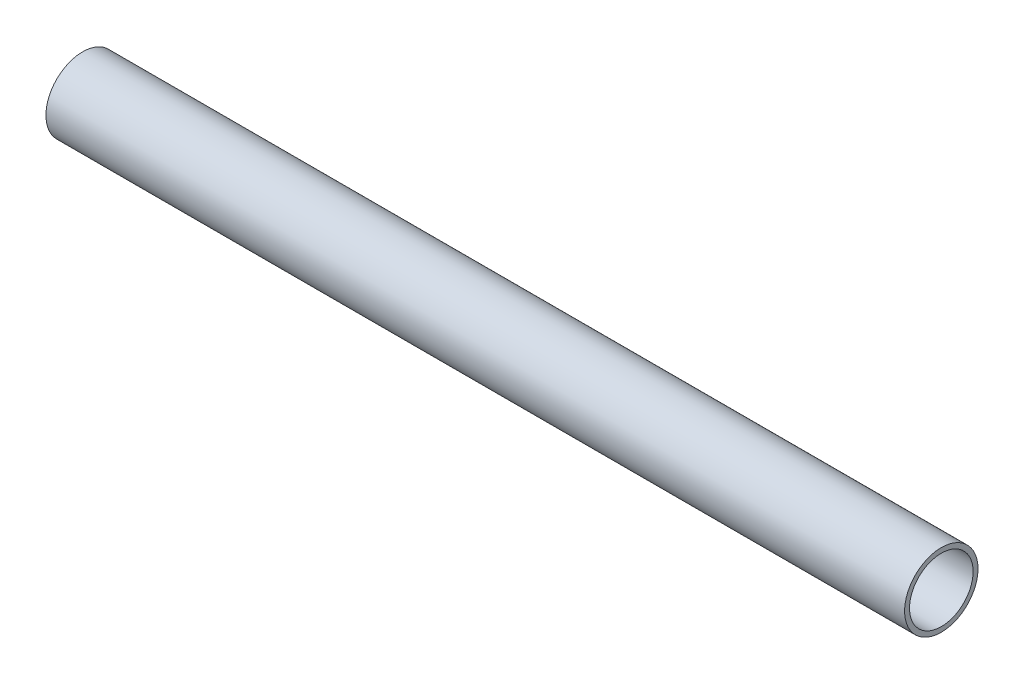
SolidWorks part; units mm, degrees
ref_plane "前视基准面" through (0, 0, 0) normal (0, 0, 1) x (1, 0, 0)
ref_plane "上视基准面" through (0, 0, 0) normal (0, 1, 0) x (1, 0, 0)
ref_plane "右视基准面" through (0, 0, 0) normal (1, 0, 0) x (0, 0, -1)
sketch "草图1" plane through (0, 0, 0) normal (1, 0, 0) x (0, 0, -1)
  circle A0 centre (0, 0) radius 7.5
  circle A1 centre (0, 0) radius 6.5
extrude "凸台-拉伸1" add sketch "草图1" along normal blind 175.5
